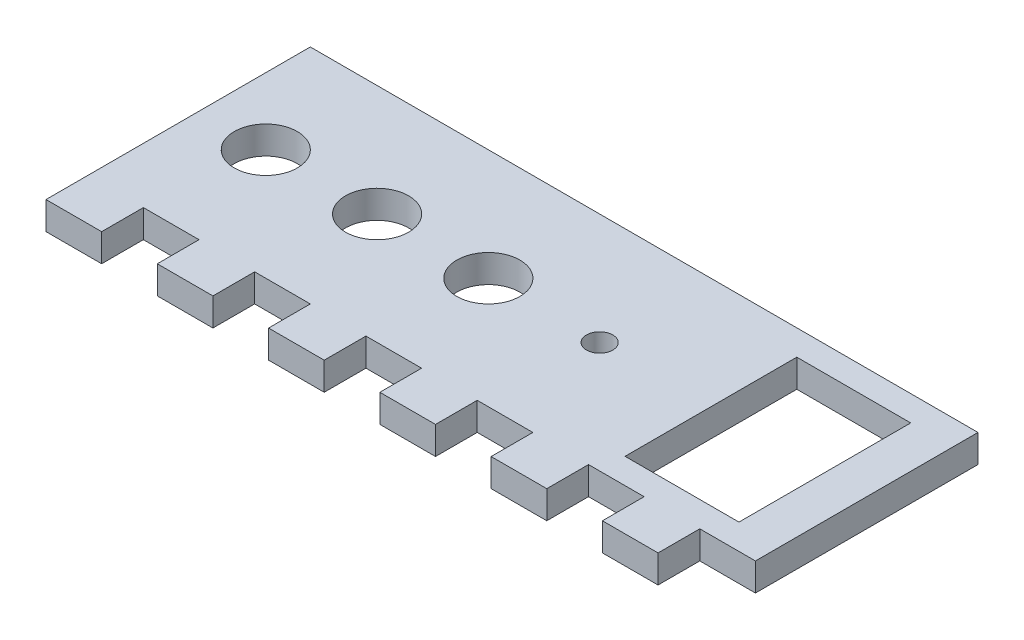
SolidWorks part; units mm, degrees
ref_plane "Front Plane" through (0, 0, 0) normal (0, 0, 1) x (1, 0, 0)
ref_plane "Top Plane" through (0, 0, 0) normal (0, 1, 0) x (1, 0, 0)
ref_plane "Right Plane" through (0, 0, 0) normal (1, 0, 0) x (0, 0, -1)
sketch "Sketch1" plane through (0, 0, 0) normal (0, 1, 0) x (1, 0, 0)
  line L0 (0, 0) -> (0, -4.7625)
  line L1 (6.35, 0) -> (12.7, 0)
  line L2 (0, 0) -> (0, 25.4)
  line L3 (0, 25.4) -> (76.2, 25.4)
  line L4 (76.2, 0) -> (76.2, 25.4)
  line L5 (58.42, 22.5) -> (71.42, 22.5)
  line L6 (58.42, 22.5) -> (58.42, 2.9)
  line L7 (58.42, 2.9) -> (71.42, 2.9)
  line L8 (71.42, 22.5) -> (71.42, 2.9)
  line L9 (0, -4.7625) -> (6.35, -4.7625)
  line L10 (6.35, -4.7625) -> (6.35, 0)
  line L11 (12.7, -4.7625) -> (19.05, -4.7625)
  line L12 (19.05, -4.7625) -> (19.05, 0)
  line L13 (12.7, 0) -> (12.7, -4.7625)
  line L14 (25.4, -4.7625) -> (31.75, -4.7625)
  line L15 (31.75, -4.7625) -> (31.75, 0)
  line L16 (25.4, 0) -> (25.4, -4.7625)
  line L17 (38.1, -4.7625) -> (44.45, -4.7625)
  line L18 (44.45, -4.7625) -> (44.45, 0)
  line L19 (38.1, 0) -> (38.1, -4.7625)
  line L20 (50.8, -4.7625) -> (57.15, -4.7625)
  line L21 (57.15, -4.7625) -> (57.15, 0)
  line L22 (50.8, 0) -> (50.8, -4.7625)
  line L23 (63.5, -4.7625) -> (69.85, -4.7625)
  line L24 (69.85, -4.7625) -> (69.85, 0)
  line L25 (63.5, 0) -> (63.5, -4.7625)
  line L26 (19.05, 0) -> (25.4, 0)
  line L27 (31.75, 0) -> (38.1, 0)
  line L28 (44.45, 0) -> (50.8, 0)
  line L29 (57.15, 0) -> (63.5, 0)
  line L30 (69.85, 0) -> (76.2, 0)
  circle A4 centre (7.62, 12.7) radius 3.6
  circle A5 centre (20.32, 12.7) radius 3.6
  circle A6 centre (33.02, 12.7) radius 3.6
  circle A7 centre (45.72, 12.7) radius 1.5
  point P27 (58.42, 12.7)
  dimension "D4" = 6.35
  dimension "D5" = 4.7625
  dimension "D6" = 6
  dimension "D15" = 7.2
  dimension "D16" = 7.2
  dimension "D17" = 7.2
  dimension "D19" = 0
  dimension "D24" = 3
  dimension "D1" = 76.2
  dimension "D2" = 25.4
  dimension "D18" = 0
  dimension "D20" = 12.7
  dimension "D21" = 12.7
  dimension "D22" = 7.62
  dimension "D23" = 12.7
  dimension "D25" = 0
  dimension "D26" = 12.7
  dimension "D27" = 13
  dimension "D28" = 19.6
  dimension "D29" = 0
  dimension "D30" = 12.7
extrude "Boss-Extrude1" add sketch "Sketch1" along normal blind 3.175
